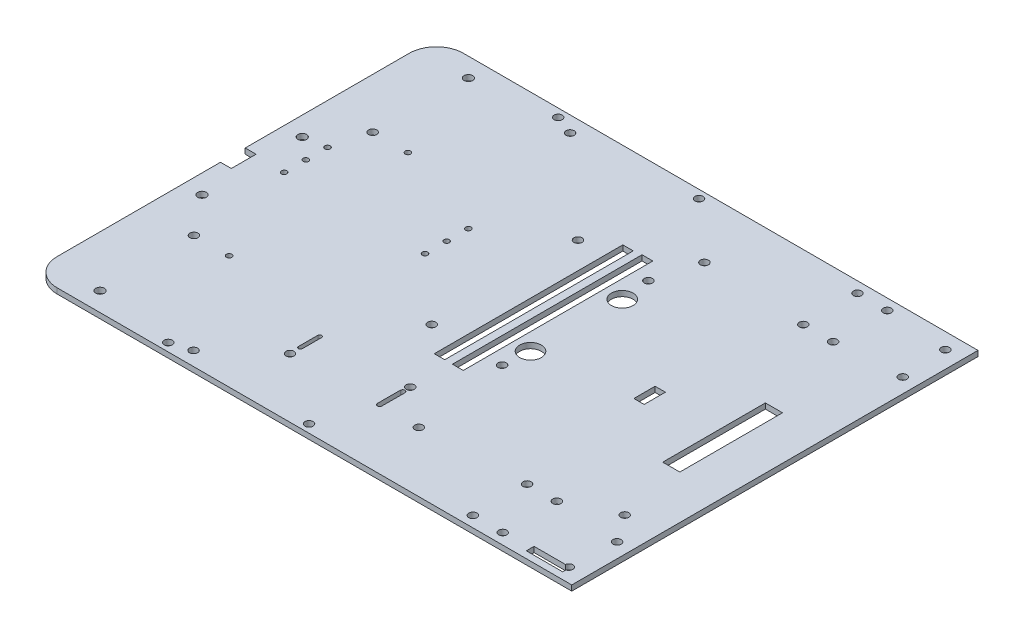
SolidWorks part; units mm, degrees
ref_plane "Front Plane" through (0, 0, 0) normal (0, 0, 1) x (1, 0, 0)
ref_plane "Top Plane" through (0, 0, 0) normal (0, 1, 0) x (1, 0, 0)
ref_plane "Right Plane" through (0, 0, 0) normal (1, 0, 0) x (0, 0, -1)
sketch "Sketch1" plane through (0, 0, 0) normal (0, 1, 0) x (1, 0, 0)
  line L1 (-100, -75) -> (100, -75)
  line L2 (-100, -75) -> (-100, 75)
  line L3 (-100, 75) -> (100, 75)
  line L4 (100, -75) -> (100, 75)
  line L5 (-100, -75) -> (100, 75) construction
  line L6 (-100, 75) -> (100, -75) construction
  point P0 (0, 0)
  dimension "D1" = 200
  dimension "D2" = 150
extrude "Boss-Extrude2" add sketch "Sketch1" along normal blind 2
sketch "Sketch2" plane through (0, 2, 0) normal (0, 1, 0) x (1, 0, 0)
  line L0 (-100, 75) -> (-100, -75) construction
  line L1 (100, 75) -> (-100, 75) construction
  line L2 (-104.3306, 0) -> (119.6071, 0) construction
  circle A0 centre (59.5, 71) radius 1.5
  circle A1 centre (59.5, 51) radius 1.5
  circle A2 centre (70.5, 71) radius 1.5
  circle A3 centre (70.5, 51) radius 1.5
  circle A4 centre (70.5, -51) radius 1.5
  circle A5 centre (70.5, -71) radius 1.5
  circle A6 centre (59.5, -51) radius 1.5
  circle A7 centre (59.5, -71) radius 1.5
  dimension "D4" = 3
  dimension "D5" = 3
  dimension "D2" = 159.5
  dimension "D7" = 20
  dimension "D8" = 170.5
  dimension "D11" = 4
extrude "Cut-Extrude5" cut sketch "Sketch2" against normal blind 10
sketch "Sketch4" plane through (0, 0, 0) normal (0, -1, 0) x (1, 0, 0)
  line L0 (-100, -75) -> (-100, 75) construction
  line L1 (-75, -48.773) -> (-75, -57.1598) construction
  circle A0 centre (-81.5, 33) radius 1.5
  circle A1 centre (-68.5, 33) radius 1
  circle A2 centre (-68.5, -33) radius 1
  circle A3 centre (-81.5, -33) radius 1.5
  circle A4 centre (-33, -19.8289) radius 1
  circle A5 centre (-33, -11.8289) radius 1
  circle A6 centre (-33, -3.8289) radius 1
  circle A7 centre (-85, -19.8289) radius 1
  circle A8 centre (-85, -11.8289) radius 1
  circle A9 centre (-85, -3.8289) radius 1
  dimension "D1" = 2
  dimension "D2" = 33
  dimension "D3" = 8.3868
  dimension "D4" = 33
  dimension "D5" = 33
  dimension "D6" = 33
  dimension "D7" = 6.5
  dimension "D8" = 6.5
  dimension "D9" = 25
  dimension "D10" = 6.5
  dimension "D11" = 6.5
extrude "Cut-Extrude6" cut sketch "Sketch4" against normal blind 10
sketch "Sketch5" plane through (0, 2, 0) normal (0, 1, 0) x (1, 0, 0)
  line L1 (100, 75) -> (-100, 75) construction
  line L2 (-100, -75) -> (100, -75) construction
  circle A0 centre (0, 72) radius 1.5
  circle A1 centre (0, -72) radius 1.5
  dimension "D1" = 3
  dimension "D2" = 3
  dimension "D3" = 3
  dimension "D4" = 3
extrude "Cut-Extrude7" cut sketch "Sketch5" against normal blind 2
sketch "Sketch9" plane through (0, 2, 0) normal (0, 1, 0) x (1, 0, 0)
  line L0 (-100, -75) -> (100, -75) construction
  line L1 (100, 75) -> (-100, 75) construction
  line L2 (0, 75) -> (0, -75) construction
  circle A0 centre (-52, 72) radius 1.5
  circle A1 centre (-52, -72) radius 1.5
  dimension "D1" = 3
  dimension "D2" = 3
  dimension "D3" = 3
  dimension "D4" = 3
  dimension "D5" = 52
  dimension "D6" = 52
extrude "Cut-Extrude8" cut sketch "Sketch9" against normal blind 2
sketch "Sketch10" plane through (0, 2, 0) normal (0, 1, 0) x (1, 0, 0)
  line L1 (-100, 75) -> (-100, -75) construction
  circle A0 centre (-93, -18.5) radius 1.6
  circle A1 centre (-93, 18.5) radius 1.6
  dimension "D1" = 3.2
  dimension "D2" = 3.2
  dimension "D3" = 7
  dimension "D4" = 7
  dimension "D5" = 37
extrude "Cut-Extrude9" cut sketch "Sketch10" against normal blind 2
sketch "Sketch11" plane through (0, 2, 0) normal (0, 1, 0) x (1, 0, 0)
  line L0 (0, 75) -> (0, -75) construction
  line L1 (100, 75) -> (-100, 75) construction
  line L2 (-100, -75) -> (100, -75) construction
  line L3 (-100, 0) -> (100, 0) construction
  line L4 (-100, 75) -> (-100, -75) construction
  line L5 (100, -75) -> (100, 75) construction
  circle A1 centre (-81.1438, -68) radius 1.6
  circle A3 centre (-81.1438, 68) radius 1.6
  dimension "D1" = 3.2
extrude "Cut-Extrude10" cut sketch "Sketch11" against normal blind 2
sketch "Sketch13" plane through (0, 2, 0) normal (0, 1, 0) x (1, 0, 0)
  line L0 (-25.9818, -49.2043) -> (-25.9818, -42.0587) construction
  line L1 (4.5443, -26.4466) -> (0.6916, -26.4466)
  line L2 (7.3953, 43.5534) -> (11.3953, 43.5534)
  line L3 (7.3953, 43.5534) -> (7.3953, -26.4466)
  line L4 (7.3953, -26.4466) -> (11.3953, -26.4466)
  line L5 (11.3953, 43.5534) -> (11.3953, -26.4466)
  line L6 (7.3953, 43.5534) -> (11.3953, -26.4466) construction
  line L7 (7.3953, -26.4466) -> (11.3953, 43.5534) construction
  line L8 (4.5443, -26.4466) -> (4.5443, 43.1661)
  line L9 (4.5443, 43.1661) -> (0.6916, 43.1661)
  line L10 (0.6916, -26.4466) -> (0.6916, 43.1661)
  line L11 (4.5443, -26.4466) -> (0.6916, 43.1661) construction
  line L12 (4.5443, 43.1661) -> (0.6916, -26.4466) construction
  line L13 (-21.9638, -42.0587) -> (-26.4638, -42.0587) construction
  line L14 (-26.6956, -49.2043) -> (-26.6956, -42.0587)
  line L15 (-25.268, -49.2043) -> (-25.268, -42.0587)
  line L17 (6.9362, -44.3862) -> (6.9117, -52.8432) construction
  line L18 (7.7693, -44.3886) -> (7.7448, -52.8456)
  line L19 (-96, 4.4407) -> (-100, 4.4407)
  line L20 (-96, 4.4407) -> (-96, -4.6931)
  line L21 (-96, -4.6931) -> (-100, -4.6931)
  line L22 (-100, 4.4407) -> (-100, -4.6931)
  line L23 (-96, 4.4407) -> (-100, -4.6931) construction
  line L24 (-96, -4.6931) -> (-100, 4.4407) construction
  line L25 (6.1031, -44.3838) -> (6.0786, -52.8407)
  line L26 (-100, 75) -> (-100, -75) construction
  line L27 (-96, -4.6931) -> (-101, -4.6931) construction
  circle A0 centre (-9.1197, -17.5809) radius 1.5
  circle A1 centre (16.8803, -17.5809) radius 1.5
  circle A2 centre (16.8803, 36.4191) radius 1.5
  circle A3 centre (-9.1197, 36.4191) radius 1.5
  circle A4 centre (17.9884, 25.655) radius 4
  circle A5 centre (17.6884, -7.9151) radius 4
  circle A6 centre (-44.8032, 69.1899) radius 1.5
  circle A7 centre (-44.8032, -69.8417) radius 1.5
  circle A8 centre (93.7565, 69.1899) radius 1.5
  circle A9 centre (93.7565, -69.8417) radius 1.5
  circle A10 centre (-25.9638, -53.0587) radius 1.5
  circle A11 centre (6.9362, -41.5587) radius 1.5
  circle A12 centre (0.6916, 43.9161) radius 0.75 construction
  arc A13 (-26.6956, -49.2043) -> (-25.268, -49.2043) centre (-25.9818, -49.2043) ccw
  arc A14 (-25.268, -42.0587) -> (-26.6956, -42.0587) centre (-25.9818, -42.0587) ccw
  arc A15 (7.7693, -44.3886) -> (6.1031, -44.3838) centre (6.9362, -44.3862) ccw
  arc A16 (6.0786, -52.8407) -> (7.7448, -52.8456) centre (6.9117, -52.8432) ccw
  point P10 (9.3953, 8.5534)
  point P19 (2.618, 8.3598)
  point P22 (17.8754, -7.9151)
  point P31 (-25.9818, -45.6315)
  point P47 (-98, -0.1262)
  point P68 (6.9239, -48.6147)
  dimension "D2" = 9.1338
  dimension "D3" = 4
  dimension "D4" = 69.6127
  dimension "D13" = 8
  dimension "D14" = 8
  dimension "D5" = 3.8526
  dimension "D10" = 4
extrude "Cut-Extrude11" cut sketch "Sketch13" against normal blind 2
sketch "Sketch15" plane through (0, 0, 0) normal (0, -1, 0) x (1, 0, 0)
  line L3 (94.1404, 69.6211) -> (80.7026, 69.6211)
  line L4 (94.1404, 69.6211) -> (94.1404, 72.4819)
  line L5 (94.1404, 72.4819) -> (80.7026, 72.4819)
  line L6 (80.7026, 69.6211) -> (80.7026, 72.4819)
  line L7 (94.1404, 69.6211) -> (80.7026, 72.4819) construction
  line L8 (94.1404, 72.4819) -> (80.7026, 69.6211) construction
  line L9 (55.6606, -3.9208) -> (51.8582, -3.9208)
  line L10 (55.6606, -3.9208) -> (55.6606, 3.9208)
  line L11 (55.6606, 3.9208) -> (51.8582, 3.9208)
  line L12 (51.8582, -3.9208) -> (51.8582, 3.9208)
  line L13 (55.6606, -3.9208) -> (51.8582, 3.9208) construction
  line L14 (55.6606, 3.9208) -> (51.8582, -3.9208) construction
  line L15 (83.8641, -18.9537) -> (77.541, -18.9537)
  line L16 (83.8641, -18.9537) -> (83.8641, 18.9537)
  line L17 (83.8641, 18.9537) -> (77.541, 18.9537)
  line L18 (77.541, -18.9537) -> (77.541, 18.9537)
  line L19 (83.8641, -18.9537) -> (77.541, 18.9537) construction
  line L20 (83.8641, 18.9537) -> (77.541, -18.9537) construction
  circle A0 centre (87.4215, 42.88) radius 1.5
  circle A1 centre (94.6053, -52.5963) radius 1.5
  circle A2 centre (94.6053, 52.8564) radius 1.5
  circle A3 centre (21.3947, -52.5963) radius 1.5
  circle A4 centre (21.3947, 52.8564) radius 1.5
  point P2 (87.4215, 71.0515)
  point P7 (53.7594, 0)
  point P12 (80.7026, 0)
  dimension "D1" = 2.8608
  dimension "D2" = 13.4379
  dimension "D3" = 7.8415
  dimension "D4" = 3.8024
  dimension "D5" = 37.9074
  dimension "D6" = 6.3231
extrude "Cut-Extrude13" cut sketch "Sketch15" against normal blind 2
fillet "Fillet1" radius 10 2 edges at (-100, 1, 75) (-100, 1, -75)
